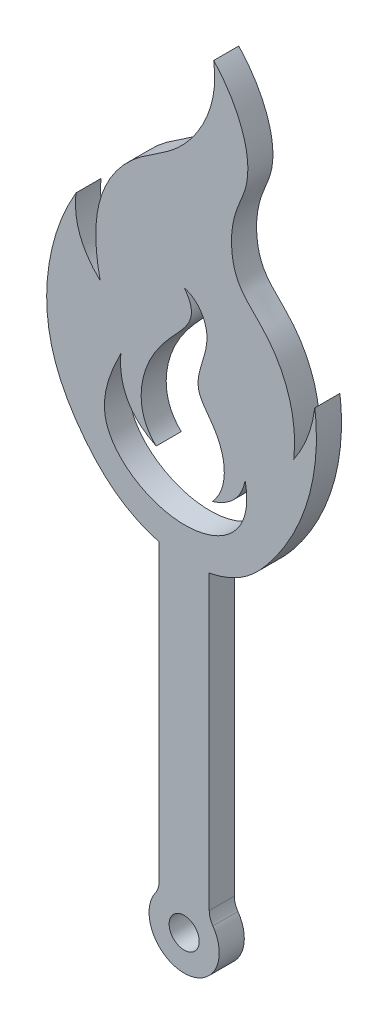
SolidWorks part; units mm, degrees
ref_plane "前视基准面" through (0, 0, 0) normal (0, 0, 1) x (1, 0, 0)
ref_plane "上视基准面" through (0, 0, 0) normal (0, 1, 0) x (1, 0, 0)
ref_plane "右视基准面" through (0, 0, 0) normal (1, 0, 0) x (0, 0, -1)
sketch "草图1" plane through (0, 0, 0) normal (0, 0, 1) x (1, 0, 0)
  line L0 (0, 0) -> (0, 33.1623) construction
  line L1 (-2.5, 3.1623) -> (-2.5, 33.1623)
  line L2 (2.5, 3.1623) -> (2.5, 33.1623)
  line L3 (-2.5, 33.1623) -> (2.5, 33.1623)
  circle A0 centre (0, 0) radius 1.5
  arc A1 (-2.8636, 2.0124) -> (2.8636, 2.0124) centre (0, 0) ccw
  arc A2 (-2.5, 3.1623) -> (-2.8636, 2.0124) centre (-4.5, 3.1623) cw
  arc A3 (2.5, 3.1623) -> (2.8636, 2.0124) centre (4.5, 3.1623) ccw
  point P11 (-2.5, 2.4495)
  point P14 (2.5, 2.4495)
  dimension "D1" = 7
  dimension "D2" = 3
  dimension "D3" = 2
  dimension "D4" = 5
  dimension "D5" = 30
extrude "凸台-拉伸1" add sketch "草图1" along normal blind 2.5
sketch "草图3" plane through (0, 0, 0) normal (0, 0, 1) x (1, 0, 0)
  line L0 (82.5866, -234.3938) -> (489.2533, -234.3938) construction
  line L1 (-530.3811, -143.2823) -> (-10.3811, -143.2823) construction
  spline S0 degree 3 poles (13.03, 51.8443) (13.7438, 46.203) (11.6033, 39.4117) (5.6945, 33.0266) (0.0631, 31.4765) (-5.9381, 33.386) (-10.4371, 37.9518) (-15.0752, 45.9902) (-13.3338, 54.2027) (-10.7829, 58.5056) knots 0 0 0 0 0.274188 0.336809 0.426489 0.54906 0.630889 0.7434 1 1 1 1
  spline S1 degree 2 poles (-10.7829, 58.5056) (-11.2162, 54.8133) (-8.3664, 52.1163) knots 0 0 0 1 1 1
  spline S2 degree 3 poles (-8.3664, 52.1163) (-8.9266, 54.5672) (-9.1462, 59.3561) (-5.3751, 64.5311) (-0.9932, 66.7788) (2.3878, 70.8598) (3.3107, 74.5379) (2.9414, 76.8014) knots 0 0 0 0 0.26425 0.46597 0.622953 0.768651 1 1 1 1
  spline S3 degree 3 poles (2.9414, 76.8014) (5.1646, 74.5003) (7.4687, 69.6647) (4.8801, 64.6135) (4.5121, 61.6286) (5.4227, 58.2018) (9.9021, 54.7178) (11.3419, 49.785) (10.9272, 46.3428) knots 0 0 0 0 0.308931 0.378034 0.507504 0.572042 0.6898 1 1 1 1
  spline S4 degree 2 poles (10.9272, 46.3428) (12.6426, 48.842) (13.03, 51.8443) knots 0 0 0 1 1 1
  spline S5 degree 3 poles (-6.3146, 46.8745) (-7.1855, 45.133) (-9.5784, 39.7713) (-0.6392, 32.9897) (7.1841, 36.7795) (6.0819, 42.0808) knots 0 0 0 0 0.245235 0.543681 1 1 1 1
  spline S6 degree 2 poles (6.0819, 42.0808) (5.5653, 39.5164) (2.8169, 38.6503) knots 0 0 0 1 1 1
  spline S7 degree 3 poles (2.8169, 38.6503) (4.4574, 40.4666) (4.1959, 44.1391) (0.3708, 48.0085) (3.2858, 52.2651) (1.414, 55.3202) (0.0002, 55.7019) knots 0 0 0 0 0.356718 0.515081 0.783238 1 1 1 1
  spline S8 degree 3 poles (0.0002, 55.7019) (1.6379, 53.6995) (-1.0805, 51.2541) (-4.4379, 46.8554) (-4.7191, 42.4289) (-2.7871, 40.6368) knots 0 0 0 0 0.313581 0.580495 1 1 1 1
  spline S9 degree 2 poles (-6.3146, 46.8745) (-6.6716, 42.5044) (-2.7871, 40.6368) knots 0 0 0 1 1 1
extrude "凸台-拉伸2" add sketch "草图3" along normal up to surface (2.5 mm away) up to face at (0, 11.8509, 2.5)
